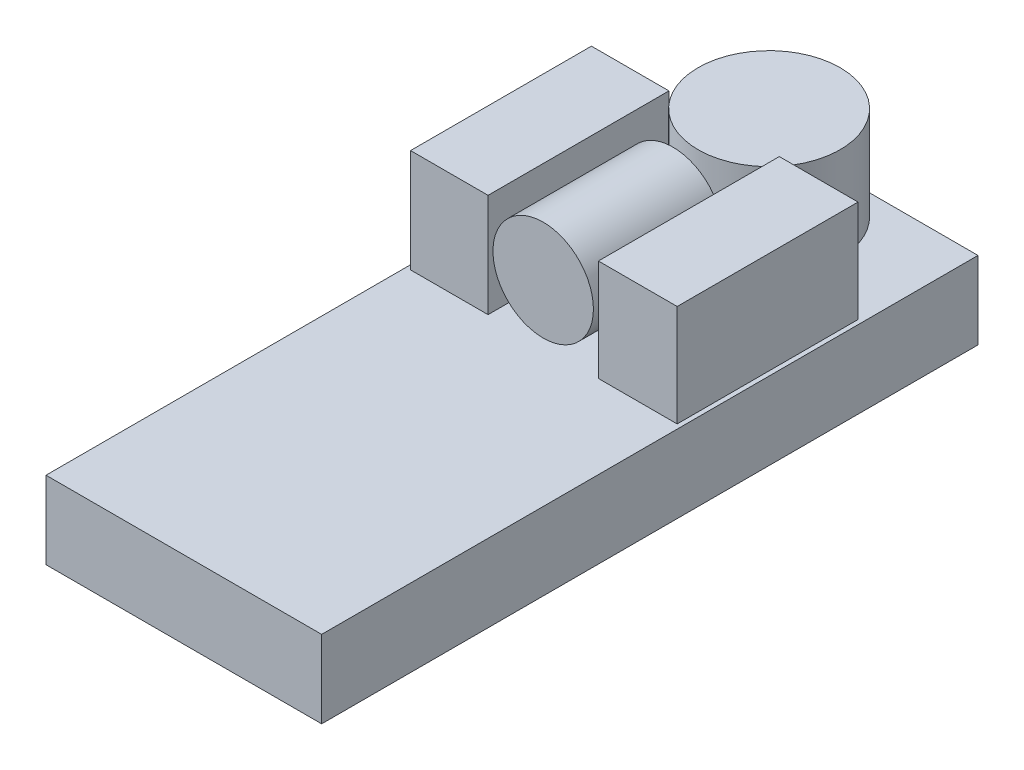
SolidWorks part; units mm, degrees
ref_plane "Front Plane" through (0, 0, 0) normal (0, 0, 1) x (1, 0, 0)
ref_plane "Top Plane" through (0, 0, 0) normal (0, 1, 0) x (1, 0, 0)
ref_plane "Right Plane" through (0, 0, 0) normal (1, 0, 0) x (0, 0, -1)
sketch "Sketch1" plane through (0, 0, 0) normal (0, 1, 0) x (1, 0, 0)
  line L1 (0, 0) -> (21.336, 0)
  line L2 (0, 0) -> (0, 50.8)
  line L3 (0, 50.8) -> (21.336, 50.8)
  line L4 (21.336, 0) -> (21.336, 50.8)
  dimension "D1" = 50.8
  dimension "D2" = 21.336
extrude "Boss-Extrude1" add sketch "Sketch1" along normal blind 6
sketch "Sketch4" plane through (0, 6, 0) normal (0, 1, 0) x (1, 0, 0)
  line L0 (21.336, 50.8) -> (0, 50.8) construction
  line L1 (0, 45.3) -> (21.336, 45.3)
  line L2 (21.336, 0) -> (21.336, 50.8) construction
  circle A0 centre (10.668, 45.3) radius 5.5
  point P9 (10.668, 45.3)
  line M6 (21.336, 50.8) -> (0, 50.8)
  dimension "D1" = 11
  dimension "D2" = 5.5
  dimension "D3" = 21.336
extrude "Boss-Extrude4" add sketch "Sketch4" along normal blind 7.254 separate body contours L1 A0 M6 | L1 A0
sketch "Sketch5" plane through (0, 6, 0) normal (0, 1, 0) x (1, 0, 0)
  line L1 (0.3465, 41.8689) -> (6.3465, 41.8689)
  line L2 (0.3465, 41.8689) -> (0.3465, 27.8689)
  line L3 (0.3465, 27.8689) -> (6.3465, 27.8689)
  line L4 (6.3465, 41.8689) -> (6.3465, 27.8689)
  point P4 (0.3465, 41.8689)
  point P6 (0, 41.8621)
  dimension "D1" = 14
  dimension "D2" = 6
  dimension "D3" = 8.9379
extrude "Boss-Extrude5" add sketch "Sketch5" along normal blind 8
sketch "Sketch7" plane through (0, 6, 0) normal (0, 1, 0) x (1, 0, 0)
  line L0 (0, 27.8621) -> (21.336, 27.8621) construction
  line L1 (21.336, 0) -> (21.336, 50.8) construction
  line L2 (0, 41.8621) -> (21.336, 41.8621) construction
  line L3 (21.336, 41.8621) -> (21.336, 27.8621)
  point P8 (0, 27.8621)
sketch "Sketch8" plane through (0, 6, 0) normal (0, 1, 0) x (1, 0, 0)
  line L0 (0, 27.8621) -> (21.336, 27.8621) construction
  line L1 (14.8939, 27.8621) -> (20.9899, 27.8621)
  line L2 (14.8939, 27.8621) -> (14.8939, 41.8621)
  line L3 (14.8939, 41.8621) -> (20.9899, 41.8621)
  line L4 (20.9899, 27.8621) -> (20.9899, 41.8621)
  point P7 (0, 0)
  dimension "D1" = 6.096
extrude "Boss-Extrude6" add sketch "Sketch8" along normal blind 7.874
ref_plane "Plane3" through (0, 0, -27.8621) normal (0, 0, 1) x (1, 0, 0)
sketch "Sketch12" plane through (0, 0, -27.8621) normal (0, 0, 1) x (1, 0, 0)
  circle A0 centre (10.6202, 10.4579) radius 3.8868
  point P2 (0, 0)
  point P3 (0, 0)
  point P7 (10.6202, 10.4579)
  point P8 (14.8939, 10.4579)
  point P9 (14.9822, 22.0917)
  point P10 (11.7134, 9.2485)
  point P13 (10.6202, 22.0917)
extrude "Boss-Extrude8" add sketch "Sketch12" against normal blind 10.048
